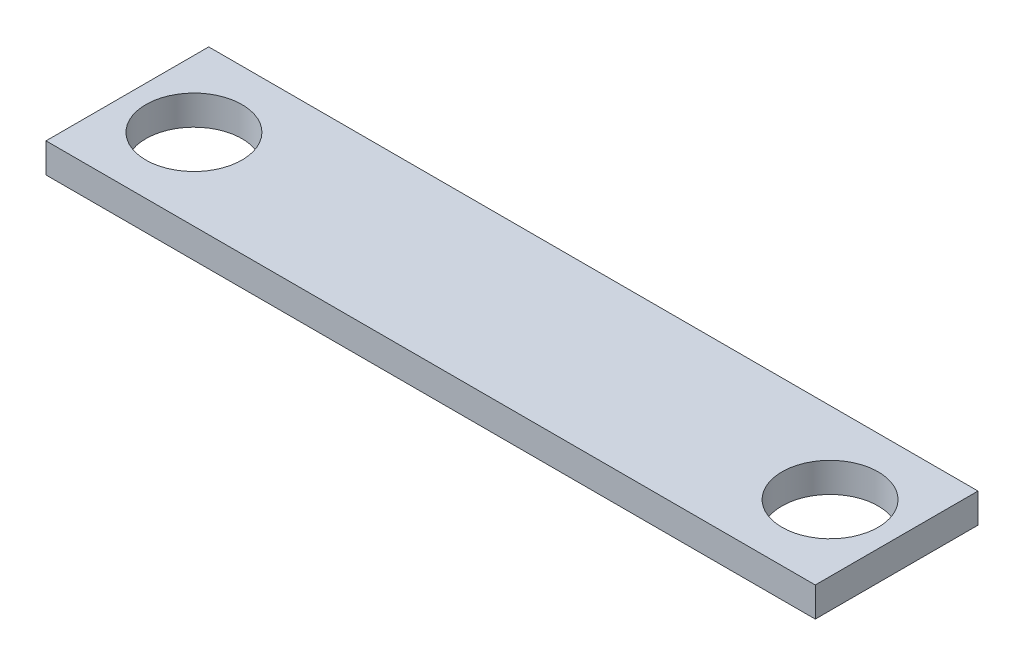
SolidWorks part; units mm, degrees
ref_plane "Front Plane" through (0, 0, 0) normal (0, 0, 1) x (1, 0, 0)
ref_plane "Top Plane" through (0, 0, 0) normal (0, 1, 0) x (1, 0, 0)
ref_plane "Right Plane" through (0, 0, 0) normal (1, 0, 0) x (0, 0, -1)
other "Configuration Table"
sketch "草图1" plane through (0, 0, 0) normal (0, 1, 0) x (1, 0, 0)
  line L1 (-260, -55) -> (260, -55)
  line L2 (-260, -55) -> (-260, 55)
  line L3 (-260, 55) -> (260, 55)
  line L4 (260, -55) -> (260, 55)
  line L5 (-260, -55) -> (260, 55) construction
  line L6 (-260, 55) -> (260, -55) construction
  circle A0 centre (-215, 0) radius 32.5
  circle A1 centre (215, 0) radius 32.5
  point P0 (0, 0)
extrude "凸台-拉伸1" add sketch "草图1" along normal blind 20
